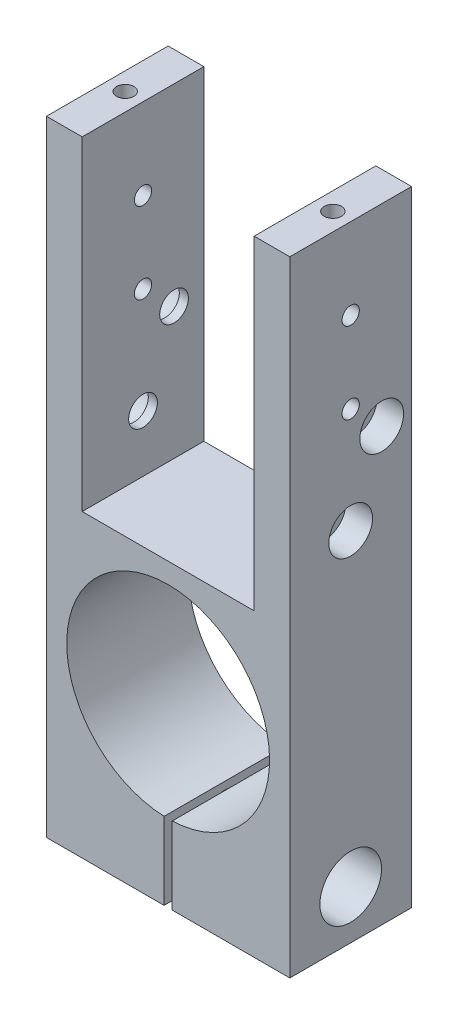
SolidWorks part; units mm, degrees
material "6061 Alloy"
ref_plane "Front Plane" through (0, 0, 0) normal (0, 0, 1) x (1, 0, 0)
ref_plane "Top Plane" through (0, 0, 0) normal (0, 1, 0) x (1, 0, 0)
ref_plane "Right Plane" through (0, 0, 0) normal (1, 0, 0) x (0, 0, -1)
sketch "Sketch1" plane through (0, 0, 0) normal (0, 1, 0) x (1, 0, 0)
  line L1 (-19.05, -9.525) -> (19.05, -9.525)
  line L2 (-19.05, -9.525) -> (-19.05, 9.525)
  line L3 (-19.05, 9.525) -> (19.05, 9.525)
  line L4 (19.05, -9.525) -> (19.05, 9.525)
  line L5 (-19.05, -9.525) -> (19.05, 9.525) construction
  line L6 (-19.05, 9.525) -> (19.05, -9.525) construction
  point P0 (0, 0)
  dimension "D1" = 38.1
  dimension "D2" = 19.05
extrude "Boss-Extrude1" add sketch "Sketch1" along normal mid plane 97.79
sketch "Sketch2" plane through (0, 0, 9.525) normal (0, 0, 1) x (1, 0, 0)
  line L0 (-19.05, 48.895) -> (19.05, 48.895) construction
  line L1 (13.462, 48.895) -> (-13.462, 48.895)
  line L2 (13.462, 48.895) -> (13.462, -1.905)
  line L3 (13.462, -1.905) -> (-13.462, -1.905)
  line L4 (-13.462, 48.895) -> (-13.462, -1.905)
  line L5 (-19.05, 48.895) -> (-19.05, -48.895) construction
  line L6 (19.05, 48.895) -> (19.05, -48.895) construction
  line L7 (-19.05, -48.895) -> (19.05, -48.895) construction
  circle A0 centre (0, -20.955) radius 15.875
  dimension "D1" = 5.588
  dimension "D2" = 5.588
  dimension "D3" = 19.05
  dimension "D4" = 27.94
extrude "Cut-Extrude1" cut sketch "Sketch2" against normal through all
hole_wizard "CBORE for #8 Socket Head Cap Screw1" positions "Sketch5" profile "Sketch4" counterbore size "#8" standard "ANSI Inch"
sketch "Sketch5" plane through (19.05, 0, 0) normal (1, 0, 0) x (0, 0, -1)
  line L0 (-9.525, 48.895) -> (9.525, 48.895) construction
  line L1 (4.8601, 18.7183) -> (4.8601, 6.985)
  line L2 (4.8601, 6.985) -> (0, 6.985)
  line L3 (0, 6.985) -> (4.8601, 6.985)
  line L5 (0, 6.985) -> (4.8601, 18.7183)
  point P0 (0, 6.985)
  point P5 (4.8601, 18.7183)
  dimension "D1" = 41.91
  dimension "D2" = 12.7
  dimension "D3" = 67.5
sketch "Sketch4" plane through (19.05, 6.985, 0) normal (0, 1, 0) x (0, 0, -1)
  line L0 (0, 0) -> (0, 38.1)
  line L1 (0, 38.1) -> (2.2479, 38.1)
  line L3 (2.2479, 38.1) -> (2.2479, 4.1656)
  line L4 (2.2479, 4.1656) -> (3.429, 4.1656)
  line L5 (3.429, 4.1656) -> (3.429, 0)
  line L7 (3.429, 0) -> (0, 0)
  line L11 (0, -6.35) -> (0, 107.95) construction
  dimension "Thru Hole Dia." = 4.4958
  dimension "Thru Hole Depth" = 38.1
  dimension "C'Bore Dia." = 6.858
  dimension "C'Bore Depth" = 4.1656
hole_wizard "#6-32 Tapped Hole1" positions "Sketch7" profile "Sketch6" tap size "#6-32" standard "ANSI Inch"
sketch "Sketch7" plane through (19.05, 0, 0) normal (1, 0, 0) x (0, 0, -1)
  line L0 (-9.525, 48.895) -> (9.525, 48.895) construction
  point P0 (0, 23.495)
  point P2 (0, 36.195)
  dimension "D1" = 12.7
  dimension "D2" = 12.7
sketch "Sketch6" plane through (19.05, 23.495, 0) normal (0, 1, 0) x (0, 0, -1)
  line L0 (0, 0) -> (0, 38.1)
  line L1 (0, 38.1) -> (1.3525, 38.1)
  line L2 (1.3525, 38.1) -> (1.3525, 0)
  line L5 (1.3525, 0) -> (0, 0)
  line L11 (0, -6.35) -> (0, 107.95) construction
  dimension "Thru Tap Drill Dia." = 2.7051
  dimension "Thru Tap Drill Depth" = 38.1
cosmetic thread "Hole Thread1" parameters "D2"=3.5052
cosmetic thread "Hole Thread2" parameters "D2"=3.5052
hole_wizard "#6-32 Tapped Hole2" positions "Sketch9" profile "Sketch8" tap size "#6-32" standard "ANSI Inch"
sketch "Sketch9" plane through (0, 48.895, 0) normal (0, 1, 0) x (1, 0, 0)
  line L0 (19.05, -9.525) -> (19.05, 9.525) construction
  point P0 (16.256, 0)
  dimension "D1" = 2.794
sketch "Sketch8" plane through (16.256, 48.895, 0) normal (1, 0, 0) x (0, 0, 1)
  line L0 (0, 0) -> (0, 11.8871)
  line L1 (0, 11.8871) -> (1.3525, 11.0744)
  line L2 (1.3525, 11.0744) -> (1.3525, 0)
  line L5 (1.3525, 0) -> (0, 0)
  line L10 (0, 11.8871) -> (-1.3526, 11.0744) construction
  line L11 (0, -6.35) -> (0, 107.95) construction
  dimension "Tap Drill Dia." = 2.7051
  dimension "Tap Drill Depth" = 11.0744
  dimension "Drill Angle" = 118
cosmetic thread "Hole Thread3" parameters "D1"=11.0744, "D2"=3.5052
hole_wizard "#8-32 Tapped Hole1" positions "Sketch15" profile "Sketch14" tap size "#8-32" standard "ANSI Inch"
sketch "Sketch15" plane through (0, -48.895, 0) normal (0, -1, 0) x (-1, 0, 0)
  line L2 (-19.05, 9.525) -> (19.05, 9.525) construction
  line L4 (19.05, -9.525) -> (-19.05, -9.525) construction
  point P6 (-10.16, 6.985)
  point P17 (-6.35, -6.985)
  dimension "D1" = 6.35
  dimension "D2" = 10.16
  dimension "D3" = 2.54
  dimension "D4" = 2.54
sketch "Sketch14" plane through (10.16, -48.895, -6.985) normal (1, 0, 0) x (0, 0, -1)
  line L0 (0, 0) -> (0, 13.3314)
  line L1 (0, 13.3314) -> (1.7272, 12.2936)
  line L2 (1.7272, 12.2936) -> (1.7272, 0)
  line L5 (1.7272, 0) -> (0, 0)
  line L10 (0, 13.3314) -> (-1.7272, 12.2936) construction
  line L11 (0, -6.35) -> (0, 107.95) construction
  dimension "Tap Drill Dia." = 3.4544
  dimension "Tap Drill Depth" = 12.2936
  dimension "Drill Angle" = 118
cosmetic thread "Hole Thread4" parameters "D1"=8.3312, "D2"=4.1656
cosmetic thread "Hole Thread5" parameters "D1"=8.3312, "D2"=4.1656
mirror "Mirror3" about plane through (0, 0, 0) normal (1, 0, 0) of "#6-32 Tapped Hole2", "CBORE for #8 Socket Head Cap Screw1", "#6-32 Tapped Hole1"
hole_wizard "CBORE for 1/4 Socket Head Cap Screw2" positions "Sketch19" profile "Sketch18" counterbore size "1/4" standard "ANSI Inch"
sketch "Sketch19" plane through (19.05, 0, 0) normal (1, 0, 0) x (0, 0, -1)
  line L0 (-9.525, -48.895) -> (9.525, -48.895) construction
  point P0 (0, -41.275)
  dimension "D1" = 7.62
sketch "Sketch18" plane through (19.05, -41.275, 0) normal (0, 1, 0) x (0, 0, -1)
  line L0 (0, 0) -> (0, 38.1)
  line L1 (0, 38.1) -> (3.2512, 38.1)
  line L3 (3.2512, 38.1) -> (3.2512, 7.112)
  line L4 (3.2512, 7.112) -> (4.826, 7.112)
  line L5 (4.826, 7.112) -> (4.826, 0)
  line L7 (4.826, 0) -> (0, 0)
  line L11 (0, -6.35) -> (0, 107.95) construction
  dimension "Thru Hole Dia." = 6.5024
  dimension "Thru Hole Depth" = 38.1
  dimension "C'Bore Dia." = 9.652
  dimension "C'Bore Depth" = 7.112
sketch "Sketch20" plane through (0, 0, 9.525) normal (0, 0, 1) x (1, 0, 0)
  line L1 (-0.635, -33.6009) -> (0.635, -33.6009)
  line L2 (-0.635, -33.6009) -> (-0.635, -51.3809)
  line L3 (-0.635, -51.3809) -> (0.635, -51.3809)
  line L4 (0.635, -33.6009) -> (0.635, -51.3809)
  line L5 (-0.635, -33.6009) -> (0.635, -51.3809) construction
  line L6 (-0.635, -51.3809) -> (0.635, -33.6009) construction
  point P0 (0, -42.4909)
  dimension "D1" = 1.27
  dimension "D2" = 17.78
extrude "Cut-Extrude4" cut sketch "Sketch20" against normal up to next
sketch "Sketch21" plane through (-19.05, 0, 0) normal (-1, 0, 0) x (0, 0, 1)
  line L1 (-5.588, -48.895) -> (5.588, -48.895)
  line L2 (-5.588, -48.895) -> (-5.588, -33.655)
  line L3 (-5.588, -33.655) -> (5.588, -33.655)
  line L4 (5.588, -48.895) -> (5.588, -33.655)
  line L5 (-5.588, -48.895) -> (5.588, -33.655) construction
  line L6 (-5.588, -33.655) -> (5.588, -48.895) construction
  point P0 (0, -41.275)
  dimension "D1" = 11.176
  dimension "D2" = 15.24
extrude "Cut-Extrude5" cut sketch "Sketch21" against normal blind 6.35
mirror "Mirror4" about plane through (0, 0, 0) normal (1, 0, 0) of "#8-32 Tapped Hole1"
